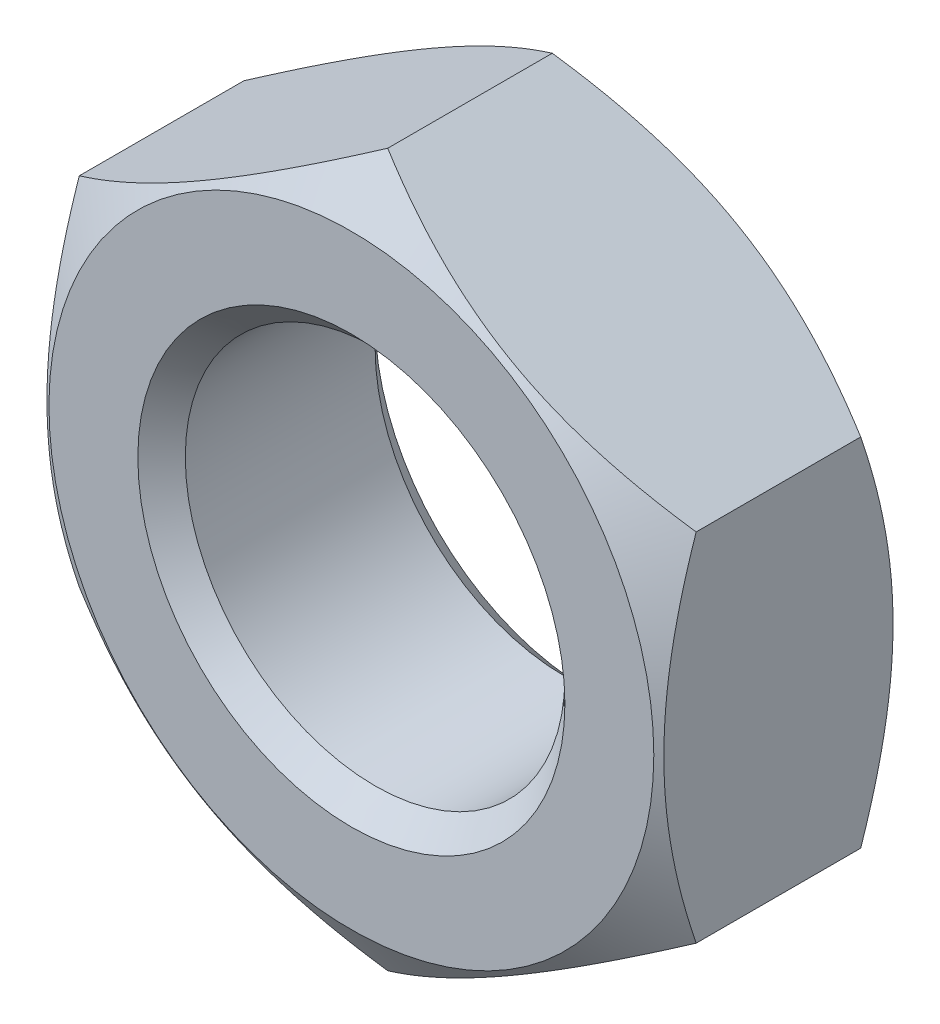
SolidWorks part; units mm, degrees
ref_plane "前视基准面" through (0, 0, 0) normal (0, 0, 1) x (1, 0, 0)
ref_plane "上视基准面" through (0, 0, 0) normal (0, 1, 0) x (1, 0, 0)
ref_plane "右视基准面" through (0, 0, 0) normal (1, 0, 0) x (0, 0, -1)
sketch "草图1" plane through (0, 0, 0) normal (0, 0, 1) x (1, 0, 0)
  line L1 (0, 7.5056) -> (-6.5, 3.7528)
  line L2 (-6.5, 3.7528) -> (-6.5, -3.7528)
  line L3 (-6.5, -3.7528) -> (0, -7.5056)
  line L4 (0, -7.5056) -> (6.5, -3.7528)
  line L5 (6.5, -3.7528) -> (6.5, 3.7528)
  line L6 (6.5, 3.7528) -> (0, 7.5056)
  circle A0 centre (0, 0) radius 4
  circle A1 centre (0, 0) radius 6.5 construction
  dimension "D1" = 8
  dimension "D2" = 13
extrude "凸台-拉伸1" add sketch "草图1" along normal blind 5
cosmetic thread "装饰螺纹线1" parameters "D1"=5, "D2"=24
ref_plane "基准面1" through (0, 0, 2.5) normal (0, 0, -1) x (-1, 0, 0)
ref_axis "基准轴1" through (0, 0, 5) along (0, 0, -1)
sketch "草图2" plane through (0, 0, 0) normal (1, 0, 0) x (0, 0, -1)
  line L0 (-4.1424, 7.6403) -> (-5.2947, 5.9385)
  line L1 (-5.2947, 5.9385) -> (-5.2947, 7.6403)
  line L2 (-5.2947, 7.6403) -> (-4.1424, 7.6403)
revolve "切除-旋转1" cut sketch "草图2" angle 360 about axis through (0, 0, 5) along (0, 0, -1)
mirror "镜向2" about plane through (0, 0, 2.5) normal (0, 0, -1) of "切除-旋转1"
chamfer "倒角1" distance 0.5 angle 45 2 edges at (4, 0, 0) (4, 0, 5)
